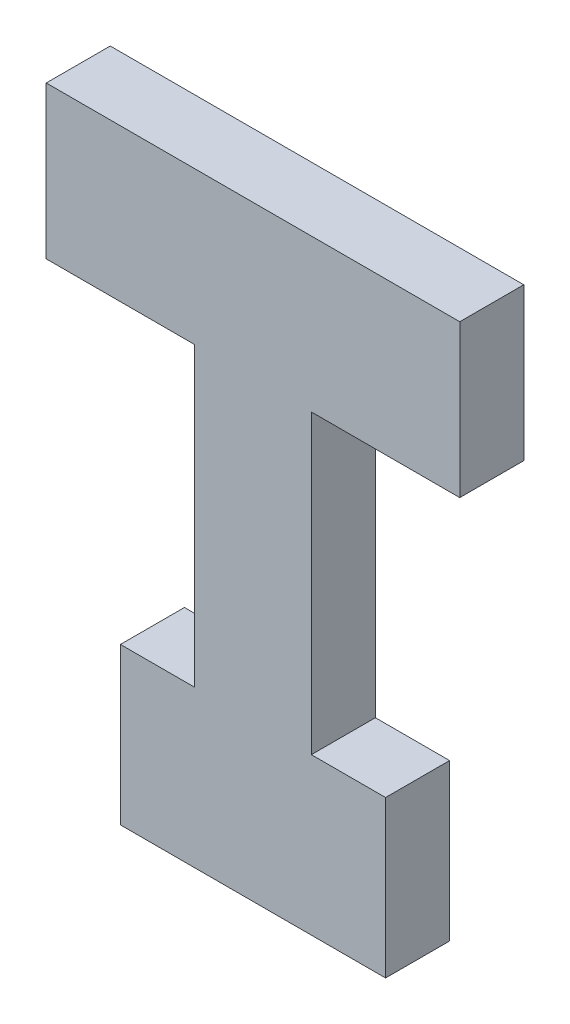
SolidWorks part; units mm, degrees
ref_plane "Спереди" through (0, 0, 0) normal (0, 0, 1) x (1, 0, 0)
ref_plane "Сверху" through (0, 0, 0) normal (0, 1, 0) x (1, 0, 0)
ref_plane "Справа" through (0, 0, 0) normal (1, 0, 0) x (0, 0, -1)
sketch "Эскиз1" plane through (0, 0, 0) normal (0, 0, 1) x (1, 0, 0)
  line L0 (32.302, 41.1116) -> (-32.302, 41.1116)
  line L1 (-32.302, 41.1116) -> (-32.302, 17.3102)
  line L2 (-32.302, 17.3102) -> (-9.1187, 17.3102)
  line L3 (-9.1187, 17.3102) -> (-9.1187, -29.0564)
  line L4 (-9.1187, -29.0564) -> (-20.7104, -29.0564)
  line L5 (-20.7104, -29.0564) -> (-20.7104, -53.4761)
  line L6 (-20.7104, -53.4761) -> (20.7104, -53.4761)
  line L7 (0, 59.9674) -> (0, -64.9131) construction
  line L8 (9.1187, -29.0564) -> (20.7104, -29.0564)
  line L9 (20.7104, -29.0564) -> (20.7104, -53.4761)
  line L10 (9.1187, 17.3102) -> (9.1187, -29.0564)
  line L11 (32.302, 17.3102) -> (9.1187, 17.3102)
  line L12 (32.302, 41.1116) -> (32.302, 17.3102)
  point P12 (0, -53.4761)
  point P16 (0, 41.1116)
extrude "Бобышка-Вытянуть1" add sketch "Эскиз1" along normal blind 10
